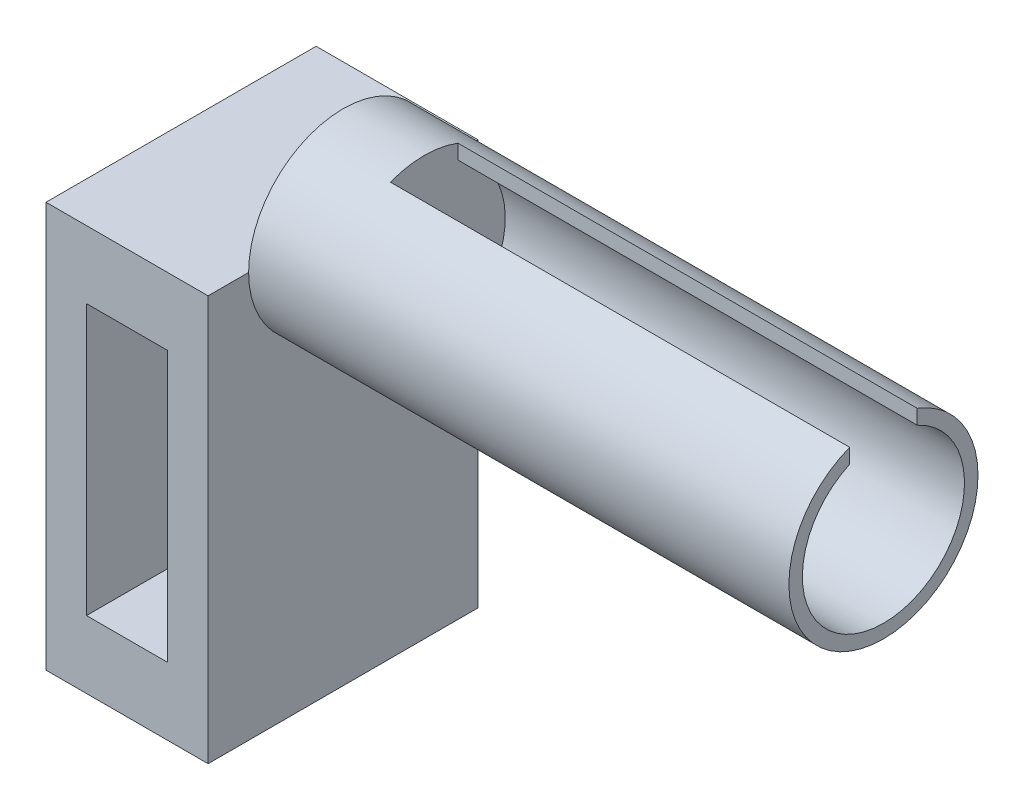
SolidWorks part; units mm, degrees
ref_plane "Front Plane" through (0, 0, 0) normal (0, 0, 1) x (1, 0, 0)
ref_plane "Top Plane" through (0, 0, 0) normal (0, 1, 0) x (1, 0, 0)
ref_plane "Right Plane" through (0, 0, 0) normal (1, 0, 0) x (0, 0, -1)
sketch "Sketch1" plane through (0, 0, 0) normal (0, 0, 1) x (1, 0, 0)
  line L1 (-3, 7.5) -> (3, 7.5)
  line L2 (-3, 7.5) -> (-3, -7.5)
  line L3 (-3, -7.5) -> (3, -7.5)
  line L4 (3, 7.5) -> (3, -7.5)
  line L5 (-3, 7.5) -> (3, -7.5) construction
  line L6 (-3, -7.5) -> (3, 7.5) construction
  point P0 (0, 0)
  dimension "D1" = 6
  dimension "10mm" = 15
extrude "Boss-Extrude1" add sketch "Sketch1" along normal blind 10
sketch "Sketch2" plane through (0, 0, 10) normal (0, 0, 1) x (1, 0, 0)
  line L1 (-1.5, 5) -> (1.5, 5)
  line L2 (-1.5, 5) -> (-1.5, -5)
  line L3 (-1.5, -5) -> (1.5, -5)
  line L4 (1.5, 5) -> (1.5, -5)
  line L5 (-1.5, 5) -> (1.5, -5) construction
  line L6 (-1.5, -5) -> (1.5, 5) construction
  point P0 (0, 0)
  dimension "D1" = 10
  dimension "3mm" = 3
extrude "Cut-Extrude1" cut sketch "Sketch2" against normal blind 7
sketch "Sketch3" plane through (3, 0, 0) normal (1, 0, 0) x (0, 0, -1)
  line L0 (-10, 7.5) -> (0, 7.5) construction
  circle A0 centre (-5, 7.5) radius 3.5
  dimension "6" = 7
extrude "Boss-Extrude2" add sketch "Sketch3" along normal blind 20
sketch "Sketch5" plane through (23, 0, 0) normal (1, 0, 0) x (0, 0, -1)
  circle A0 centre (-5, 7.5) radius 3
  point P3 (0, 0)
  dimension "D1" = 6
extrude "Cut-Extrude2" cut sketch "Sketch5" against normal blind 17
sketch "Sketch6" plane through (23, 0, 0) normal (1, 0, 0) x (0, 0, -1)
  line L1 (-3.75, 10) -> (-6.25, 10)
  line L2 (-3.75, 10) -> (-3.75, 11)
  line L3 (-3.75, 11) -> (-6.25, 11)
  line L4 (-6.25, 10) -> (-6.25, 11)
  line L5 (-3.75, 10) -> (-6.25, 11) construction
  line L6 (-3.75, 11) -> (-6.25, 10) construction
  circle A0 centre (-5, 7.5) radius 3 construction
  circle A1 centre (-5, 7.5) radius 3 construction
  point P0 (-5, 10.5)
  dimension "D1" = 2.5
  dimension "1mm" = 1
extrude "Cut-Extrude3" cut sketch "Sketch6" against normal blind 17
